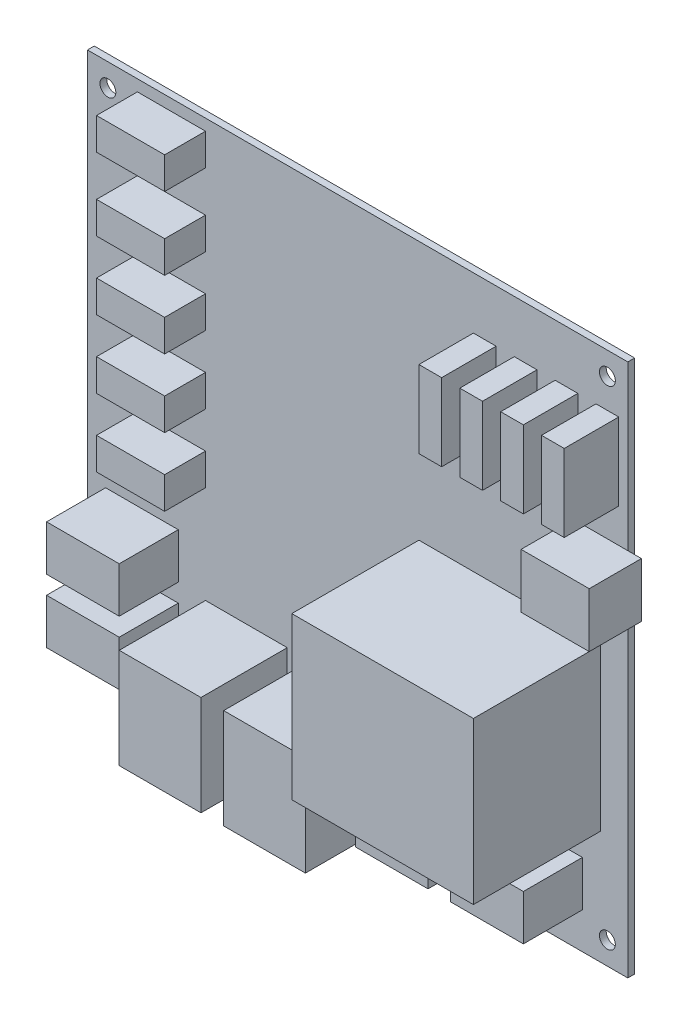
SolidWorks part; units mm, degrees
ref_plane "Спереди" through (0, 0, 0) normal (0, 0, 1) x (1, 0, 0)
ref_plane "Сверху" through (0, 0, 0) normal (0, 1, 0) x (1, 0, 0)
ref_plane "Справа" through (0, 0, 0) normal (1, 0, 0) x (0, 0, -1)
sketch "Эскиз1" plane through (0, 0, 0) normal (0, 0, 1) x (1, 0, 0)
  line L0 (-50.6236, 30.2879) -> (105.8936, 30.2879) construction
  line L1 (-26.798, 35.2879) -> (92.202, 35.2879)
  line L2 (-26.798, 35.2879) -> (-26.798, -82.2121)
  line L3 (-26.798, -82.2121) -> (92.202, -82.2121)
  line L4 (92.202, 35.2879) -> (92.202, -82.2121)
  line L5 (-22.298, 39.3649) -> (-22.298, -88.0681) construction
  line L6 (-31.9626, -77.2121) -> (114.4676, -77.2121) construction
  line L7 (87.702, 40.7098) -> (87.702, -89.413) construction
  line L8 (32.702, 35.2879) -> (32.702, -82.2121) construction
  line L9 (-26.798, -23.4621) -> (92.202, -23.4621) construction
  circle A0 centre (-22.298, 30.2879) radius 1.75
  circle A1 centre (87.702, 30.2879) radius 1.75
  circle A2 centre (87.702, -77.2121) radius 1.75
  circle A3 centre (-22.298, -77.2121) radius 1.75
  dimension "D5" = 3.5
  dimension "D6" = 3.5
  dimension "D9" = 3.5
  dimension "D10" = 3.5
  dimension "D1" = 119
  dimension "D2" = 117.5
  dimension "D3" = 110
  dimension "D4" = 55
  dimension "D7" = 107.5
  dimension "D8" = 53.75
extrude "Бобышка-Вытянуть1" add sketch "Эскиз1" along normal blind 1.5
sketch "Эскиз2" plane through (0, 0, 1.5) normal (0, 0, 1) x (1, 0, 0)
  line L1 (80.202, -0.7121) -> (95.202, -0.7121)
  line L2 (80.202, -0.7121) -> (80.202, -12.7121)
  line L3 (80.202, -12.7121) -> (95.202, -12.7121)
  line L4 (95.202, -0.7121) -> (95.202, -12.7121)
  line L7 (92.202, -82.2121) -> (92.202, 35.2879) construction
  line L8 (92.202, 35.2879) -> (-26.798, 35.2879) construction
  dimension "D1" = 15
  dimension "D2" = 12
  dimension "D3" = 3
  dimension "D4" = 36
extrude "Бобышка-Вытянуть2" add sketch "Эскиз2" along normal blind 11.5
sketch "Эскиз4" plane through (0, 0, 1.5) normal (0, 0, 1) x (1, 0, 0)
  line L0 (92.202, -82.2121) -> (92.202, -12.7121) construction
  line L1 (46.202, -21.7121) -> (86.202, -21.7121)
  line L2 (46.202, -21.7121) -> (46.202, -57.2121)
  line L3 (46.202, -57.2121) -> (86.202, -57.2121)
  line L4 (86.202, -21.7121) -> (86.202, -57.2121)
  line L5 (-26.798, -82.2121) -> (92.202, -82.2121) construction
  dimension "D1" = 40
  dimension "D2" = 35.5
  dimension "D3" = 6
  dimension "D4" = 25
extrude "Бобышка-Вытянуть3" add sketch "Эскиз4" along normal blind 28
sketch "Эскиз5" plane through (0, 0, 1.5) normal (0, 0, 1) x (1, 0, 0)
  line L1 (92.202, -82.2121) -> (92.202, -12.7121) construction
  line L2 (85.202, 23.7879) -> (90.202, 23.7879)
  line L3 (85.202, 23.7879) -> (85.202, 6.7879)
  line L4 (85.202, 6.7879) -> (90.202, 6.7879)
  line L5 (90.202, 23.7879) -> (90.202, 6.7879)
  line L6 (76.202, 23.7879) -> (81.202, 23.7879)
  line L7 (76.202, 23.7879) -> (76.202, 6.7879)
  line L8 (76.202, 6.7879) -> (81.202, 6.7879)
  line L9 (81.202, 23.7879) -> (81.202, 6.7879)
  line L10 (67.202, 23.7879) -> (72.202, 23.7879)
  line L11 (67.202, 23.7879) -> (67.202, 6.7879)
  line L12 (67.202, 6.7879) -> (72.202, 6.7879)
  line L13 (72.202, 23.7879) -> (72.202, 6.7879)
  line L14 (58.202, 23.7879) -> (63.202, 23.7879)
  line L15 (58.202, 23.7879) -> (58.202, 6.7879)
  line L16 (58.202, 6.7879) -> (63.202, 6.7879)
  line L18 (63.202, 23.7879) -> (63.202, 6.7879)
  line L19 (92.202, 35.2879) -> (-26.798, 35.2879) construction
  dimension "D1" = 5
  dimension "D2" = 5
  dimension "D3" = 5
  dimension "D4" = 5
  dimension "D5" = 4
  dimension "D6" = 4
  dimension "D7" = 4
  dimension "D8" = 2
  dimension "D9" = 17
  dimension "D10" = 17
  dimension "D11" = 17
  dimension "D12" = 17
  dimension "D13" = 11.5
extrude "Бобышка-Вытянуть4" add sketch "Эскиз5" along normal blind 12
sketch "Эскиз6" plane through (0, 0, 1.5) normal (0, 0, 1) x (1, 0, 0)
  line L0 (92.202, -82.2121) -> (92.202, -12.7121) construction
  line L1 (45.202, -64.2121) -> (61.202, -64.2121)
  line L2 (45.202, -64.2121) -> (45.202, -74.2121)
  line L3 (45.202, -74.2121) -> (61.202, -74.2121)
  line L4 (61.202, -64.2121) -> (61.202, -74.2121)
  line L5 (66.202, -64.2121) -> (82.202, -64.2121)
  line L6 (66.202, -64.2121) -> (66.202, -74.2121)
  line L7 (66.202, -74.2121) -> (82.202, -74.2121)
  line L8 (82.202, -64.2121) -> (82.202, -74.2121)
  line L9 (-26.798, -82.2121) -> (92.202, -82.2121) construction
  dimension "D1" = 10
  dimension "D2" = 10
  dimension "D3" = 16
  dimension "D4" = 16
  dimension "D5" = 5
  dimension "D6" = 10
  dimension "D7" = 8
  dimension "D8" = 8
extrude "Бобышка-Вытянуть5" add sketch "Эскиз6" along normal blind 13
sketch "Эскиз7" plane through (0, 0, 1.5) normal (0, 0, 1) x (1, 0, 0)
  line L0 (-26.798, -82.2121) -> (92.202, -82.2121) construction
  line L1 (22.202, -56.7121) -> (40.202, -56.7121)
  line L2 (22.202, -56.7121) -> (22.202, -78.7121)
  line L3 (22.202, -78.7121) -> (40.202, -78.7121)
  line L4 (40.202, -56.7121) -> (40.202, -78.7121)
  line L5 (-0.798, -56.7121) -> (17.202, -56.7121)
  line L6 (-0.798, -56.7121) -> (-0.798, -78.7121)
  line L7 (-0.798, -78.7121) -> (17.202, -78.7121)
  line L8 (17.202, -56.7121) -> (17.202, -78.7121)
  line L9 (92.202, -82.2121) -> (92.202, -12.7121) construction
  dimension "D1" = 18
  dimension "D2" = 18
  dimension "D3" = 22
  dimension "D4" = 22
  dimension "D5" = 5
  dimension "D6" = 3.5
  dimension "D7" = 3.5
  dimension "D8" = 52
extrude "Бобышка-Вытянуть6" add sketch "Эскиз7" along normal blind 19
sketch "Эскиз8" plane through (0, 0, 1.5) normal (0, 0, 1) x (1, 0, 0)
  line L0 (-26.798, 35.2879) -> (-26.798, -82.2121) construction
  line L1 (-15.798, 16.7879) -> (-0.798, 16.7879)
  line L2 (-15.798, 16.7879) -> (-15.798, 9.7879)
  line L3 (-15.798, 9.7879) -> (-0.798, 9.7879)
  line L4 (-0.798, 16.7879) -> (-0.798, 9.7879)
  line L5 (-15.798, 1.7879) -> (-0.798, 1.7879)
  line L6 (-15.798, 1.7879) -> (-15.798, -5.2121)
  line L7 (-15.798, -5.2121) -> (-0.798, -5.2121)
  line L8 (-0.798, 1.7879) -> (-0.798, -5.2121)
  line L9 (-15.798, -13.2121) -> (-0.798, -13.2121)
  line L10 (-15.798, -13.2121) -> (-15.798, -20.2121)
  line L11 (-15.798, -20.2121) -> (-0.798, -20.2121)
  line L12 (-0.798, -13.2121) -> (-0.798, -20.2121)
  line L13 (-15.798, -28.2121) -> (-0.798, -28.2121)
  line L14 (-15.798, -28.2121) -> (-15.798, -35.2121)
  line L15 (-15.798, -35.2121) -> (-0.798, -35.2121)
  line L16 (-0.798, -28.2121) -> (-0.798, -35.2121)
  line L17 (-15.798, 32.7879) -> (-0.798, 32.7879)
  line L18 (-15.798, 32.7879) -> (-15.798, 25.7879)
  line L19 (-15.798, 25.7879) -> (-0.798, 25.7879)
  line L20 (-0.798, 32.7879) -> (-0.798, 25.7879)
  line L21 (92.202, 35.2879) -> (-26.798, 35.2879) construction
  dimension "D1" = 7
  dimension "D2" = 7
  dimension "D3" = 7
  dimension "D4" = 7
  dimension "D5" = 7
  dimension "D6" = 15
  dimension "D7" = 15
  dimension "D8" = 15
  dimension "D9" = 15
  dimension "D10" = 15
  dimension "D11" = 9
  dimension "D12" = 8
  dimension "D13" = 8
  dimension "D14" = 8
  dimension "D15" = 11
  dimension "D16" = 11
  dimension "D17" = 11
  dimension "D18" = 11
  dimension "D19" = 11
  dimension "D20" = 2.5
extrude "Бобышка-Вытянуть7" add sketch "Эскиз8" along normal blind 9
sketch "Эскиз9" plane through (0, 0, 1.5) normal (0, 0, 1) x (1, 0, 0)
  line L0 (-26.798, -82.2121) -> (92.202, -82.2121) construction
  line L1 (-22.798, -46.2121) -> (-6.798, -46.2121)
  line L2 (-22.798, -46.2121) -> (-22.798, -56.2121)
  line L3 (-22.798, -56.2121) -> (-6.798, -56.2121)
  line L4 (-6.798, -46.2121) -> (-6.798, -56.2121)
  line L5 (-22.798, -60.2121) -> (-6.798, -60.2121)
  line L6 (-22.798, -60.2121) -> (-22.798, -70.2121)
  line L7 (-22.798, -70.2121) -> (-6.798, -70.2121)
  line L8 (-6.798, -60.2121) -> (-6.798, -70.2121)
  line L9 (-26.798, 35.2879) -> (-26.798, -82.2121) construction
  dimension "D1" = 16
  dimension "D2" = 16
  dimension "D3" = 10
  dimension "D4" = 10
  dimension "D5" = 4
  dimension "D6" = 12
  dimension "D7" = 4
  dimension "D8" = 4
extrude "Бобышка-Вытянуть9" add sketch "Эскиз9" along normal blind 13
